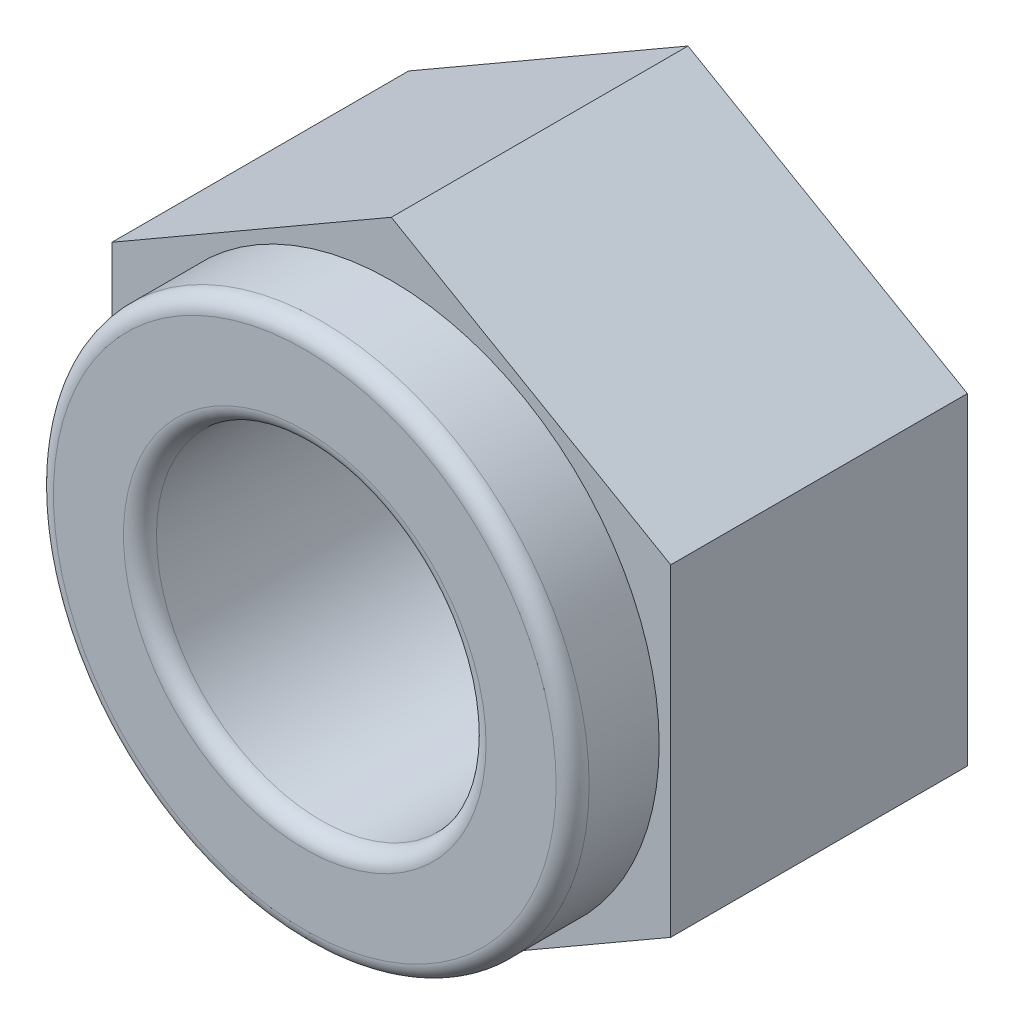
SolidWorks part; units mm, degrees
ref_plane "前视基准面" through (0, 0, 0) normal (0, 0, 1) x (1, 0, 0)
ref_plane "上视基准面" through (0, 0, 0) normal (0, 1, 0) x (1, 0, 0)
ref_plane "右视基准面" through (0, 0, 0) normal (1, 0, 0) x (0, 0, -1)
sketch "草图1" plane through (0, 0, 0) normal (0, 0, 1) x (1, 0, 0)
  line L1 (-3.39, -1.9572) -> (0, -3.9144)
  line L2 (0, -3.9144) -> (3.39, -1.9572)
  line L3 (3.39, -1.9572) -> (3.39, 1.9572)
  line L4 (3.39, 1.9572) -> (0, 3.9144)
  line L5 (0, 3.9144) -> (-3.39, 1.9572)
  line L6 (-3.39, 1.9572) -> (-3.39, -1.9572)
  circle A0 centre (0, 0) radius 3.39 construction
  dimension "D1" = 6.78
extrude "凸台-拉伸1" add sketch "草图1" along normal blind 3.6
sketch "草图2" plane through (0, 0, 3.6) normal (0, 0, 1) x (1, 0, 0)
  circle A0 centre (0, 0) radius 3.25
  circle A1 centre (0, 0) radius 2
  dimension "D1" = 4
  dimension "D2" = 6.5
extrude "凸台-拉伸2" add sketch "草图2" along normal blind 1.05
sketch "草图3" plane through (0, 0, 3.6) normal (0, 0, 1) x (1, 0, 0)
  circle A0 centre (0, 0) radius 2
extrude "切除-拉伸1" cut sketch "草图3" against normal through all
fillet "圆角1" radius 0.2 1 edges at (2, 0, 4.65)
fillet "圆角2" radius 0.2 1 edges at (3.25, 0, 4.65)
